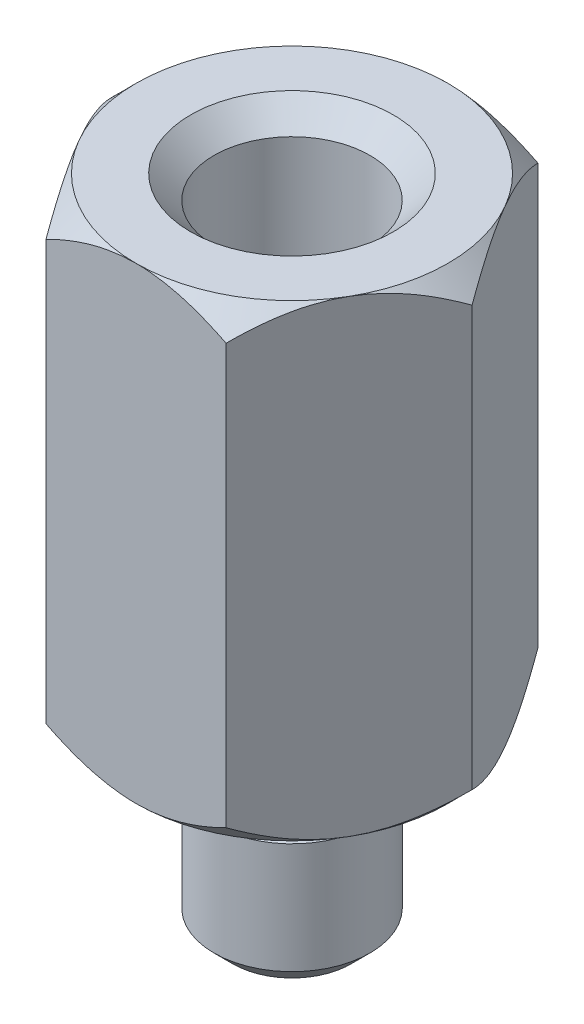
SolidWorks part; units mm, degrees
material "황동"
ref_plane "정면" through (0, 0, 0) normal (0, 0, 1) x (1, 0, 0)
ref_plane "윗면" through (0, 0, 0) normal (0, 1, 0) x (1, 0, 0)
ref_plane "우측면" through (0, 0, 0) normal (1, 0, 0) x (0, 0, -1)
sketch "Sketch1" plane through (0, 0, 0) normal (0, 1, 0) x (1, 0, 0)
  line L1 (1.1547, 2) -> (-1.1547, 2)
  line L2 (-1.1547, 2) -> (-2.3094, 0)
  line L3 (-2.3094, 0) -> (-1.1547, -2)
  line L4 (-1.1547, -2) -> (1.1547, -2)
  line L5 (1.1547, -2) -> (2.3094, 0)
  line L6 (2.3094, 0) -> (1.1547, 2)
  circle A0 centre (0, 0) radius 2 construction
  dimension "D" = 4
extrude "Extrude1" add sketch "Sketch1" along normal blind 6
sketch "Sketch2" plane through (0, 0, 0) normal (1, 0, 0) x (0, 0, -1)
  line L0 (0.76, 0) -> (0.76, -0.5)
  line L1 (0, 0) -> (0.76, 0)
  line L2 (0, 0) -> (0, -2.4)
  line L3 (0, -2.4) -> (0.76, -2.4)
  line L4 (1, -0.74) -> (1, -2.16)
  line L5 (0.76, -0.5) -> (1, -0.74)
  line L6 (1, -2.16) -> (0.76, -2.4)
  dimension "D1" = 0.24
  dimension "D2" = 45
  dimension "D3" = 45
  dimension "D4" = 0.5
  dimension "D5" = 2.4
  dimension "M" = 2
revolve "Revolve1" add sketch "Sketch2" angle 360 about L2
sketch "Sketch3" plane through (0, 0, 0) normal (1, 0, 0) x (0, 0, -1)
  line L0 (1.3, 6) -> (1, 5.7)
  line L1 (0, 6) -> (1.3, 6)
  line L2 (0, 6) -> (0, 1.7991)
  line L3 (0, 1.7991) -> (1, 2.4)
  line L4 (1, 5.7) -> (1, 2.4)
  line L5 (0, 6) -> (2, 6) construction
  dimension "D5" = 2.4
  dimension "D1" = 45
  dimension "D2" = 0.3
  dimension "D3" = 2
  dimension "D4" = 59
revolve "Cut-Revolve1" cut sketch "Sketch3" angle 360 about L2
sketch "Sketch4" plane through (0, 0, 0) normal (1, 0, 0) x (0, 0, -1)
  line L0 (2, 6) -> (4.5, 6)
  line L1 (4.5, 6) -> (4.5, 3.5)
  line L2 (4.5, 3.5) -> (2, 6)
  line L3 (2, 0) -> (4.5, 0)
  line L4 (4.5, 0) -> (4.5, 2.5)
  line L5 (4.5, 2.5) -> (2, 0)
  line L6 (1.3, 6) -> (-1.3, 6) construction
  line L7 (0, 0) -> (0, 6) construction
  dimension "D3" = 1
  dimension "D1" = 2
revolve "Cut-Revolve3" cut sketch "Sketch4" angle 360 about L7
equation "\"Mass\"= \"SW-질량\" / 1000"
equation "\"D5@Sketch2\"= 1.2 * \"M@Sketch2\""
equation "\"D1@Sketch2\"= 0.12 * \"M@Sketch2\""
equation "\"D2@Sketch3\"= 0.15 * \"M@Sketch2\""
equation "\"D5@Sketch3\"= 0.4 * \"L@Extrude1\""
equation "\"D3@Sketch3\"= \"M@Sketch2\""
equation "\"D1@Sketch4\"= 0.5 * \"D@Sketch1\""
